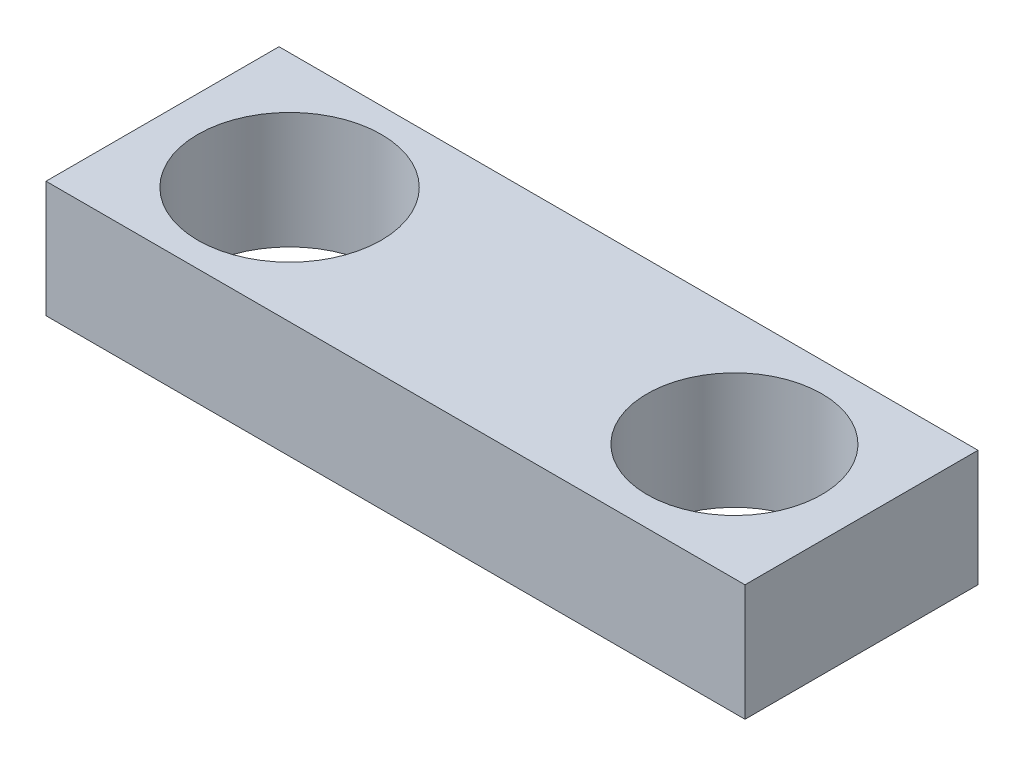
SolidWorks part; units mm, degrees
material "ABS PC"
ref_plane "Front Plane" through (0, 0, 0) normal (0, 0, 1) x (1, 0, 0)
ref_plane "Top Plane" through (0, 0, 0) normal (0, 1, 0) x (1, 0, 0)
ref_plane "Right Plane" through (0, 0, 0) normal (1, 0, 0) x (0, 0, -1)
sketch "Sketch1" plane through (0, 0, 0) normal (0, 1, 0) x (1, 0, 0)
  line L1 (-19.05, -6.35) -> (19.05, -6.35)
  line L2 (-19.05, -6.35) -> (-19.05, 6.35)
  line L3 (-19.05, 6.35) -> (19.05, 6.35)
  line L4 (19.05, -6.35) -> (19.05, 6.35)
  line L5 (-19.05, -6.35) -> (19.05, 6.35) construction
  line L6 (-19.05, 6.35) -> (19.05, -6.35) construction
  circle A0 centre (-12.1247, 0) radius 5
  circle A1 centre (12.1247, 0) radius 4.7625
  point P4 (0, 0)
  dimension "D1" = 10
  dimension "D2" = 9.525
  dimension "D3" = 38.1
  dimension "D4" = 12.1247
  dimension "D5" = 12.1247
  dimension "D6" = 12.7
extrude "Boss-Extrude1" add sketch "Sketch1" along normal blind 6.35
equation "\"D5@Sketch1\"=\"D4@Sketch1\""
